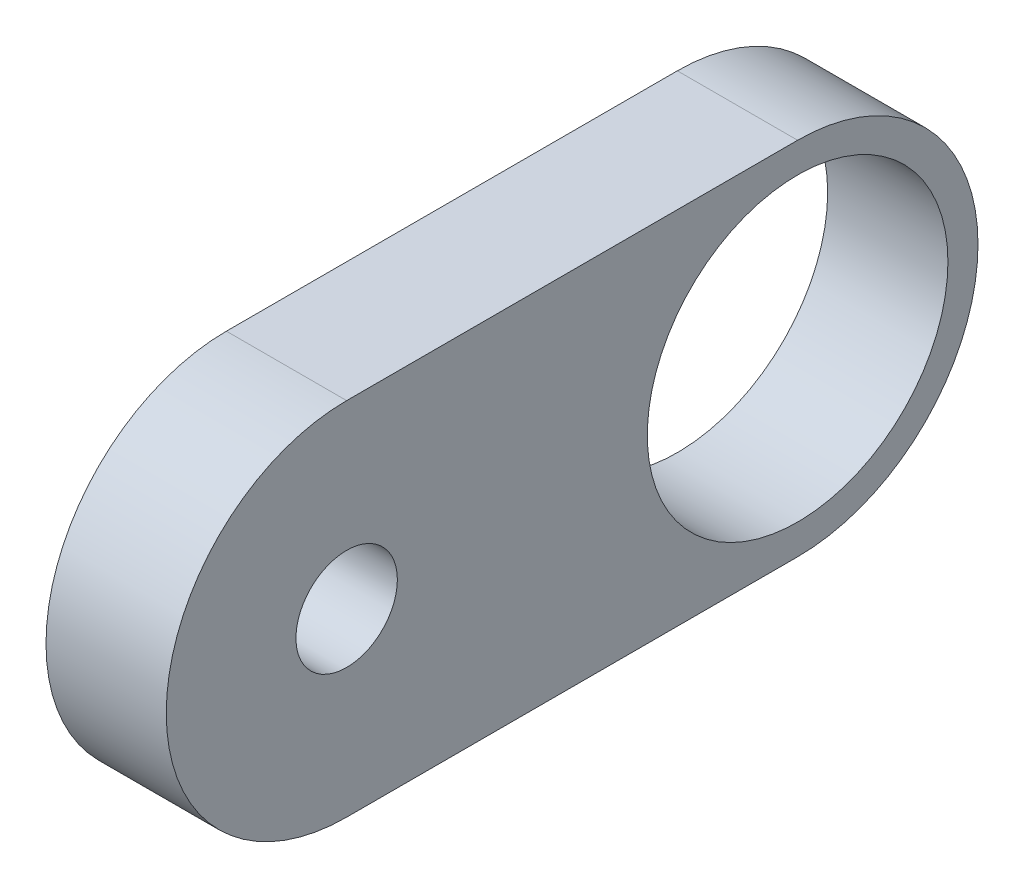
SolidWorks part; units mm, degrees
material "Ti-6Al-4VSolution treated and aged (SS)"
ref_plane "Front Plane" through (0, 0, 0) normal (1, 0, 0) x (0, 1, 0)
ref_plane "Top Plane" through (0, 0, 0) normal (0, 0, 1) x (0, 1, 0)
ref_plane "Right Plane" through (0, 0, 0) normal (0, 1, 0) x (-1, 0, 0)
sketch "Sketch1" plane through (0, 0, 0) normal (1, 0, 0) x (0, 1, 0)
  line L0 (-60.8736, 15.3619) -> (-60.8736, -22.7381)
  line L1 (-30.3936, -22.7381) -> (-30.3936, 15.3619)
  arc A0 (-60.8736, 15.3619) -> (-30.3936, 15.3619) centre (-45.6336, 15.3619) cw
  arc A1 (-60.8736, -22.7381) -> (-30.3936, -22.7381) centre (-45.6336, -22.7381) ccw
  circle A2 centre (-45.6336, -22.7381) radius 12.7
  circle A3 centre (-45.6336, 15.3619) radius 4.285
  dimension "D1" = 25.4
  dimension "D2" = 8.57
  dimension "D3" = 30.48
  dimension "D4" = 38.1
extrude "Boss-Extrude1" add sketch "Sketch1" along normal blind 10.16
equation "\"d_max\"= 1.000"
equation "\"F\"= 1200"
equation "\"YieldStr\"= 120000.0006"
equation "\"SF\"= 4"
equation "\"A_min\"= ( \"F\" * \"SF\" ) / ( \"YieldStr\" )"
equation "\"x\"= 0.10"
equation "\"y\"= \"A_min\" / \"x\""
equation "\"width\"= 2 * ( ( \"d_max\" / 2 ) + \"x\" )"
equation "\"d_top\"= 0.3374"
equation "\"D1@Sketch1\"=\"d_max\""
equation "\"D2@Sketch1\"=\"d_top\""
equation "\"D3@Sketch1\"=\"width\""
equation "\"r_max\"= \"d_max\" / 2"
equation "\"D4@Sketch1\"=\"d_max\"+\"r_max\""
equation "\"D1@Boss-Extrude1\"=\"y\""
